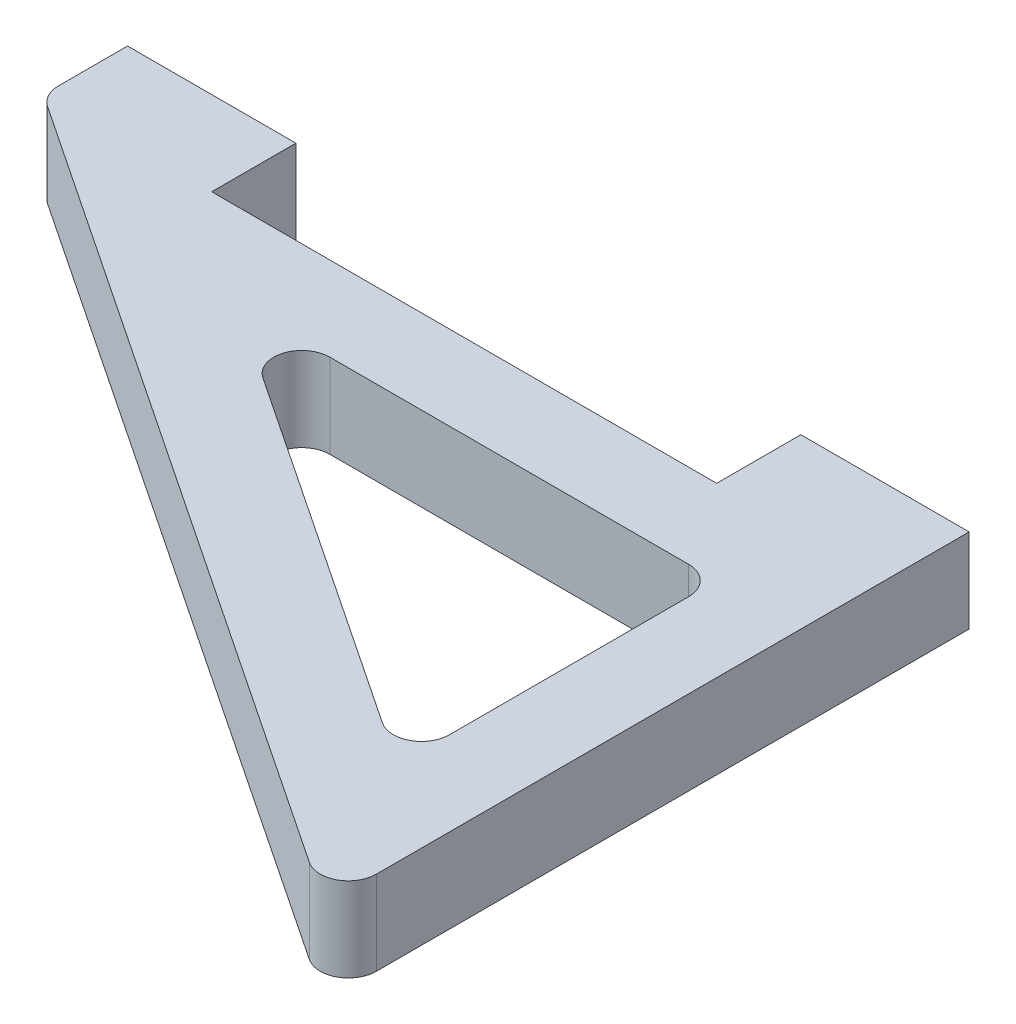
SolidWorks part; units mm, degrees
ref_plane "Front Plane" through (0, 0, 0) normal (0, 0, 1) x (1, 0, 0)
ref_plane "Top Plane" through (0, 0, 0) normal (0, 1, 0) x (1, 0, 0)
ref_plane "Right Plane" through (0, 0, 0) normal (1, 0, 0) x (0, 0, -1)
sketch "Sketch1" plane through (0, 0, 0) normal (0, 1, 0) x (1, 0, 0)
  line L0 (-15, -1.5) -> (15, -21.5)
  line L1 (-15, 1.5) -> (15, 1.5)
  line L2 (-15, 1.5) -> (-15, -1.5)
  line L3 (-15, -1.5) -> (15, -1.5)
  line L4 (15, 1.5) -> (15, -1.5)
  line L5 (-15, 1.5) -> (15, -1.5) construction
  line L6 (-15, -1.5) -> (15, 1.5) construction
  line L7 (15, -21.5) -> (15, -1.5)
  line L8 (0, 1.5) -> (0, -1.5) construction
  line L9 (-9, 1.5) -> (-9, -1.5)
  line L10 (9, 1.5) -> (9, -1.5)
  point P0 (0, 0)
  dimension "D1" = 30
  dimension "D2" = 3
  dimension "D3" = 20
  dimension "D4" = 6
extrude "Boss-Extrude1" add sketch "Sketch1" along normal blind 3 contours L0 L7 L3 | L9 L1 L2 L3 | L1 L10 L3 L4
sketch "Sketch2" plane through (0, 3, 0) normal (0, 1, 0) x (1, 0, 0)
  line L0 (-15, -1.5) -> (15, -1.5)
  line L2 (15, -1.5) -> (15, -21.5)
  line L3 (15, -21.5) -> (-15, -1.5)
  line L4 (-5.0917, -4.5) -> (12, -4.5)
  line L5 (12, -4.5) -> (12, -15.8944)
  line L6 (12, -15.8944) -> (-5.0917, -4.5)
  line L7 (15, -21.5) -> (15, 1.5) construction
  point P3 (-15, -1.5)
  point P4 (15, -1.5)
  point P10 (-15, -1.5)
  point P15 (15, -31.5)
  point P16 (15, -31.5)
  dimension "D1" = 3
extrude "Cut-Extrude1" cut sketch "Sketch2" against normal up to next contours L6 L5 L4
fillet "Fillet1" radius 1 5 edges at (15, 1.5, 21.5) (12, 1.5, 15.8944) (12, 1.5, 4.5) (-5.0917, 1.5, 4.5) (-15, 1.5, 1.5)
